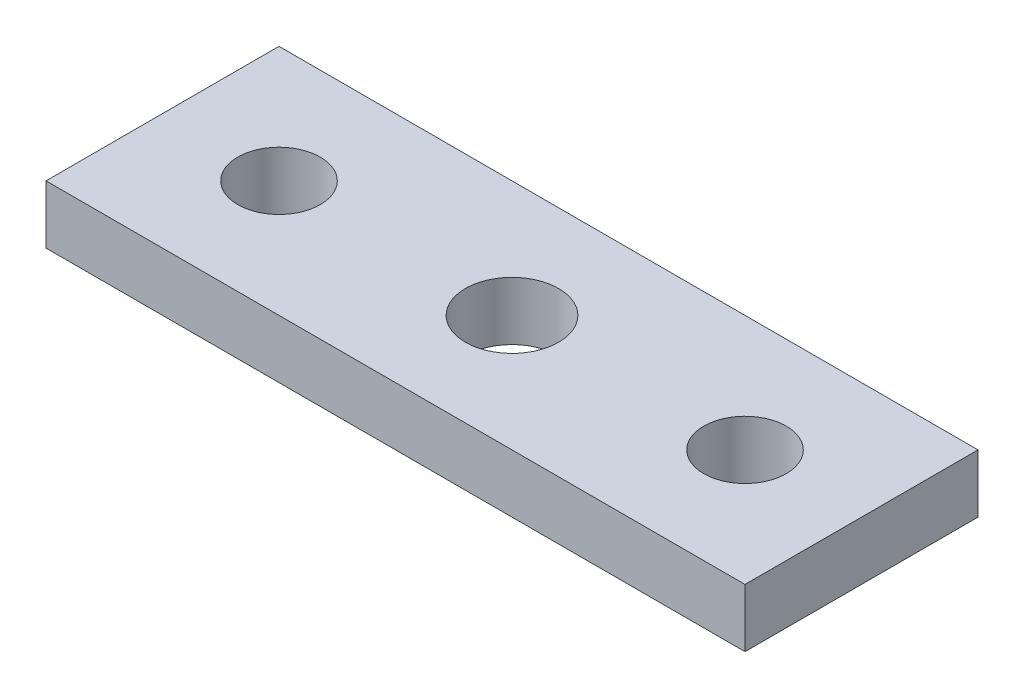
SolidWorks part; units mm, degrees
ref_plane "Front Plane" through (0, 0, 0) normal (0, 0, 1) x (1, 0, 0)
ref_plane "Top Plane" through (0, 0, 0) normal (0, 1, 0) x (1, 0, 0)
ref_plane "Right Plane" through (0, 0, 0) normal (1, 0, 0) x (0, 0, -1)
sketch "Sketch1" plane through (0, 0, 0) normal (0, 1, 0) x (1, 0, 0)
  line L1 (-19.05, 6.35) -> (19.05, 6.35)
  line L2 (-19.05, 6.35) -> (-19.05, -6.35)
  line L3 (-19.05, -6.35) -> (19.05, -6.35)
  line L4 (19.05, 6.35) -> (19.05, -6.35)
  dimension "D1" = 38.1
  dimension "D2" = 12.7
  dimension "D3" = 19.05
  dimension "D4" = 6.35
extrude "Boss-Extrude1" add sketch "Sketch1" along normal blind 3.175
sketch "Sketch2" plane through (0, 3.175, 0) normal (0, 1, 0) x (1, 0, 0)
  circle A0 centre (0, 0) radius 2.54
  dimension "D1" = 5.08
extrude "Cut-Extrude1" cut sketch "Sketch2" against normal through all
hole_wizard "#8 Clearance Hole1" positions "Sketch4" profile "Sketch3" hole size "#8" standard "ANSI Inch" end condition through all
sketch "Sketch4" plane through (0, 3.175, 0) normal (0, 1, 0) x (1, 0, 0)
  point P0 (-12.7, 0)
  point P2 (12.7, 0)
sketch "Sketch3" plane through (-12.7, 3.175, 0) normal (1, 0, 0) x (0, 0, 1)
  line L0 (0, 0) -> (0, 3.175)
  line L1 (0, 3.175) -> (2.2479, 3.175)
  line L2 (2.2479, 3.175) -> (2.2479, 0)
  line L5 (2.2479, 0) -> (0, 0)
  line L11 (0, -6.35) -> (0, 107.95) construction
  dimension "Thru Hole Dia." = 4.4958
  dimension "Thru Hole Depth" = 3.175
